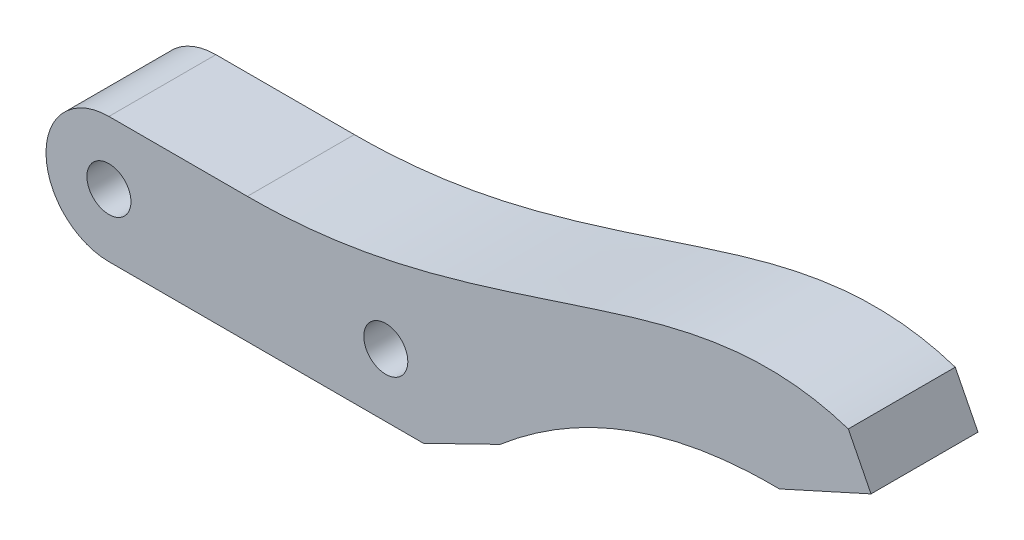
SolidWorks part; units mm, degrees
material "Cast Alloy Steel"
ref_plane "Front Plane" through (0, 0, 0) normal (0, 0, 1) x (1, 0, 0)
ref_plane "Top Plane" through (0, 0, 0) normal (0, 1, 0) x (1, 0, 0)
ref_plane "Right Plane" through (0, 0, 0) normal (1, 0, 0) x (0, 0, -1)
sketch "Sketch1" plane through (0, 0, 0) normal (0, 0, 1) x (1, 0, 0)
  line L1 (-16, 5) -> (16, 5)
  line L2 (-16, 5) -> (-16, -5)
  line L3 (-16, -5) -> (16, -5)
  line L4 (16, 5) -> (16, -5)
  line L5 (-16, 5) -> (16, -5) construction
  line L6 (-16, -5) -> (16, 5) construction
  circle A0 centre (11, 0) radius 1.75
  circle A2 centre (-11, 0) radius 1.75
  circle A3 centre (-11, 0) radius 5
  circle A4 centre (11, 0) radius 5
  point P0 (0, 0)
  dimension "D1" = 3.5
  dimension "D3" = 10
  dimension "D2" = 10
  dimension "D4" = 22
extrude "Boss-Extrude1" add sketch "Sketch1" along normal blind 8.5 contours A3 A2 | A4 L1 A3 L3 | A4 A0
sketch "Sketch2" plane through (0, 0, 8.5) normal (0, 0, 1) x (1, 0, 0)
  line L0 (-11, 5) -> (11, 5) construction
  line L1 (0, 5) -> (11, 5)
  line L2 (11, -5) -> (13.99, -5)
  line L3 (13.99, -5) -> (20.08, -2.0297)
  line L4 (42.27, 6) -> (49.557, 9.3014)
  line L5 (49.557, 9.3014) -> (47.75, 12.87)
  line L6 (-11, -5) -> (11, -5) construction
  arc A0 (11, -5) -> (11, 5) centre (11, 0) ccw construction
  arc A1 (11, -5) -> (11, 5) centre (11, 0) ccw
  spline S0 degree 3 poles (0, 5) (8.2118, 5.0033) (16.5452, 7.4034) (31.8293, 12.4366) (40.7136, 15.2055) (47.75, 12.87) knots 0 0 0 0 0.466101 0.566101 1 1 1 1
  spline S1 degree 2 poles (20.08, -2.0297) (29.7387, 6.1883) (42.27, 6) knots 0 0 0 1 1 1
  dimension "D1" = 4
  dimension "D2" = 17.87
  dimension "D3" = 26
  dimension "D4" = 11
  dimension "D5" = 36.75
  dimension "D6" = 8
  dimension "D7" = 2.99
  dimension "D8" = 9.45
  dimension "D9" = 15.03
  dimension "D10" = 9.08
  dimension "D11" = 13.52
  dimension "D12" = 20.52
  dimension "D13" = 31.27
extrude "Boss-Extrude2" add sketch "Sketch2" against normal blind 8.5
